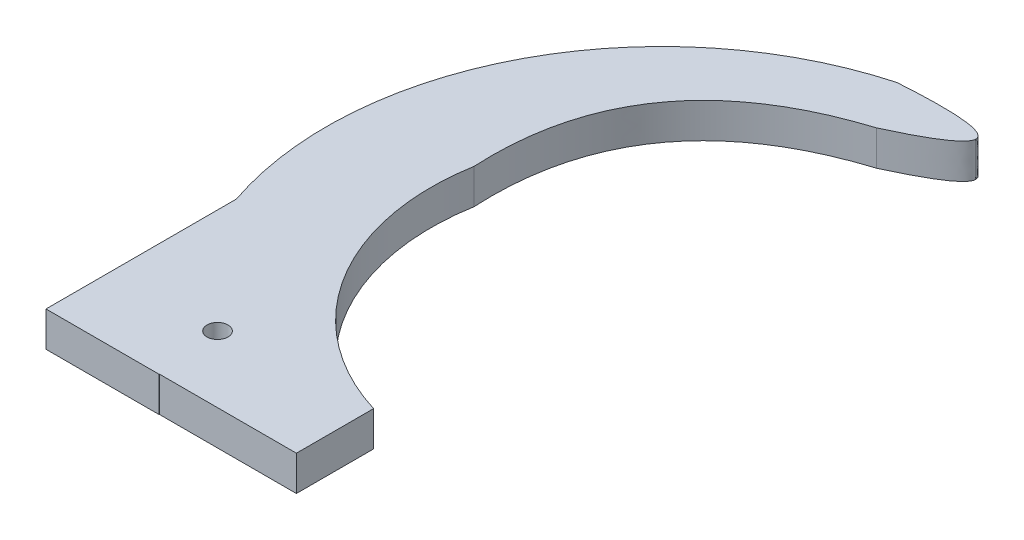
SolidWorks part; units mm, degrees
ref_plane "Front Plane" through (0, 0, 0) normal (0, 0, 1) x (1, 0, 0)
ref_plane "Top Plane" through (0, 0, 0) normal (0, 1, 0) x (1, 0, 0)
ref_plane "Right Plane" through (0, 0, 0) normal (1, 0, 0) x (0, 0, -1)
sketch "Sketch1" plane through (0, 0, 0) normal (0, 1, 0) x (1, 0, 0)
  line L0 (0, 48) -> (0, 33)
  line L1 (-45.4667, 13.2678) -> (5.0067, 13.2678)
  line L2 (-45.4667, 13.2678) -> (-45.4667, -47.4725)
  line L3 (-45.4667, -47.4725) -> (5.0067, -47.4725)
  line L4 (5.0067, 13.2678) -> (5.0067, -47.4725)
  line L5 (-45.4667, -33) -> (25.7862, -33)
  line L6 (-45.4667, -33) -> (-45.4667, -107.9997)
  line L7 (-45.4667, -107.9997) -> (25.7862, -107.9997)
  line L8 (25.7862, -33) -> (25.7862, -107.9997)
  line L9 (0, -33) -> (0, -48)
  circle A0 centre (0, 0) radius 33
  circle A1 centre (0, 0) radius 48
  dimension "D1" = 66
  dimension "D2" = 96
extrude "Boss-Extrude1" add sketch "Sketch1" along normal mid plane 5 contours L1 A1 L2 L5 A0 | L0 A1 L1 A0 | A1 L5 L2 L3 L4 | A1 L4 L3 L6 L7 L8 | L4 A1 L8 L5 | L5 A1 L9 | L9 A1 L4 L5 | A1 L2 L5
sketch "Sketch2" plane through (0, 2.5, 0) normal (0, 1, 0) x (1, 0, 0)
  line L1 (-29.2862, -42.5955) -> (9.7138, -42.5955)
  line L2 (-29.2862, -42.5955) -> (-29.2862, -61.5955)
  line L3 (-29.2862, -61.5955) -> (9.7138, -61.5955)
  line L4 (9.7138, -42.5955) -> (9.7138, -61.5955)
  dimension "D1" = 39
  dimension "D2" = 19
extrude "Cut-Extrude2" cut sketch "Sketch2" against normal through all
sketch "Sketch6" plane through (0, 2.5, 0) normal (0, 1, 0) x (1, 0, 0)
  line L5 (-45.4667, -15.3875) -> (-45.4667, -107.9997) construction
  line L6 (9.7138, -42.5955) -> (-29.2862, -42.5955) construction
  circle A2 centre (-30.4667, -33.0955) radius 1.5
  dimension "D5" = 3
  dimension "D6" = 15
  dimension "D8" = 9.5
extrude "Cut-Extrude11" cut sketch "Sketch6" against normal through all
sketch "Sketch11" plane through (0, 2.5, 0) normal (0, 1, 0) x (1, 0, 0)
  line L0 (-8.4912, 43.9058) -> (-8.4912, 31.8889) construction
  line L1 (-8.4912, 39.2208) -> (-8.4912, 31.8889)
  line L2 (-8.4912, 31.8889) -> (-32.514, 5.6424)
  arc A2 (0, 33) -> (0, -33) centre (0, 0) ccw construction
  spline S0 degree 2 poles (-32.514, 5.6424) (-33.8828, 31.2071) (-8.4912, 39.2208) knots 0 0 0 1 1 1
extrude "Cut-Extrude17" cut sketch "Sketch11" against normal blind 10
sketch "Sketch16" plane through (0, 2.5, 0) normal (0, 1, 0) x (1, 0, 0)
  line L4 (0, 48) -> (0, 33) construction
  line L5 (-12.6738, 46.2966) -> (-14.0893, 56.8471)
  line L6 (-14.0893, 56.8471) -> (1.9936, 53.8947)
  line L7 (0, 48) -> (0, 33)
  line L8 (1.9936, 53.8947) -> (6.6165, 45.5036)
  line L9 (6.6165, 45.5036) -> (5.2957, 36.5687)
  line L10 (5.2957, 36.5687) -> (3.1202, 30.8192)
  line L11 (3.1202, 30.8192) -> (-12.2635, 30.8192)
  line L12 (-12.2635, 30.8192) -> (-8.4912, 39.2208)
  arc A0 (0, 48) -> (-45.4667, -15.3875) centre (0, 0) ccw construction
  spline S0 degree 2 poles (-8.4912, 39.2208) (10.3763, 47.8692) (-12.6738, 46.2966) knots 0 0 0 1 1 1
  line M5 (-8.4912, 39.2208) -> (-8.4912, 31.8889)
  arc M6 (-8.4912, 31.8889) -> (0, 33) centre (0, 0) cw
  line M7 (0, 33) -> (0, 48)
  arc M8 (0, 48) -> (-45.4667, -15.3875) centre (0, 0) ccw
sketch "Sketch17" plane through (0, 2.5, 0) normal (0, 1, 0) x (1, 0, 0)
  line L0 (25.7862, -33) -> (25.7862, -107.9997) construction
  line L1 (-51.8054, -113.0048) -> (25.7862, -113.0048)
  line L2 (-51.8054, -113.0048) -> (-51.8054, -42.6369)
  line L3 (-51.8054, -42.6369) -> (25.7862, -42.6369)
  line L4 (25.7862, -113.0048) -> (25.7862, -42.6369)
  line L5 (-51.8054, -113.0048) -> (25.7862, -42.6369) construction
  line L6 (-51.8054, -42.6369) -> (25.7862, -113.0048) construction
  point P0 (-13.0096, -77.8208)
  point P7 (-51.8054, -113.0048)
extrude "Cut-Extrude19" cut sketch "Sketch17" against normal blind 10 contours L2 L1 L4 L3
extrude "Cut-Extrude20" cut sketch "Sketch16" against normal blind 10 contours S0 M5 M6 M7 | S0 M7 M8
sketch "Sketch18" plane through (0, 2.5, 0) normal (0, 1, 0) x (1, 0, 0)
  line L1 (27.7665, -30.4899) -> (-9.6828, -30.4899)
  line L2 (27.7665, -30.4899) -> (27.7665, -45.3056)
  line L3 (27.7665, -45.3056) -> (-9.6828, -45.3056)
  line L4 (-9.6828, -30.4899) -> (-9.6828, -45.3056)
  line L5 (27.7665, -30.4899) -> (-9.6828, -45.3056) construction
  line L6 (27.7665, -45.3056) -> (-9.6828, -30.4899) construction
  point P0 (9.0418, -37.8977)
  point P5 (27.7665, -30.4899)
extrude "Cut-Extrude21" cut sketch "Sketch18" against normal blind 10 contours L2 L1 L4 L3
